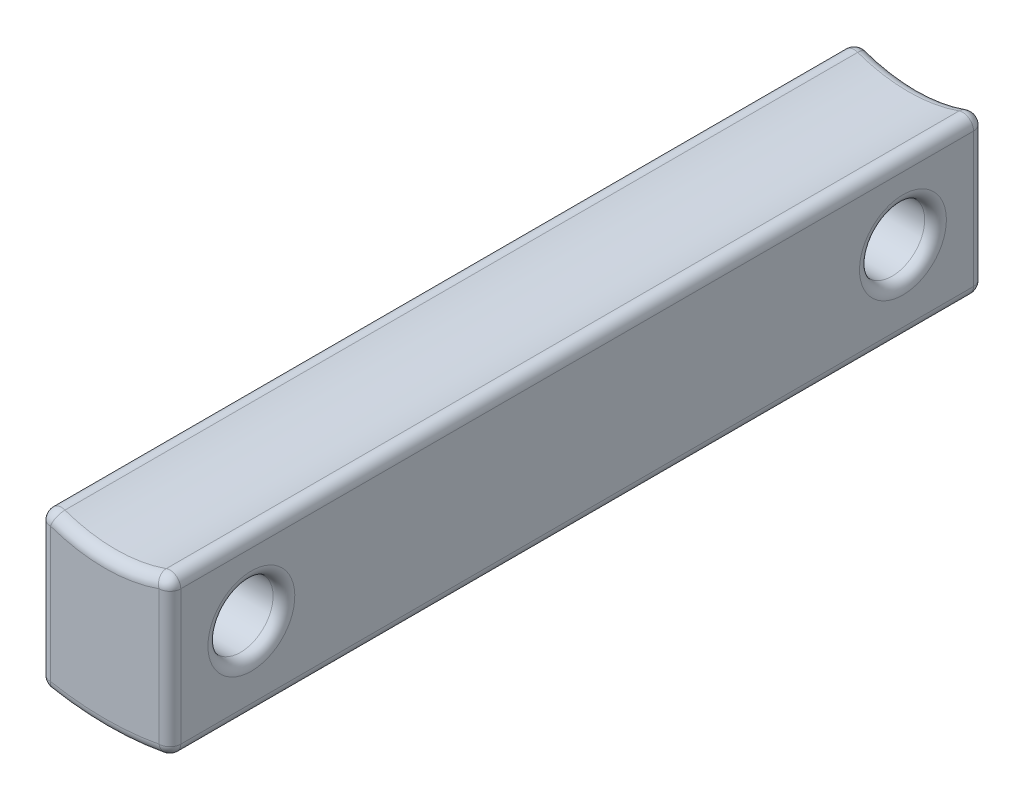
SolidWorks part; units mm, degrees
ref_plane "前视基准面" through (0, 0, 0) normal (0, 0, 1) x (1, 0, 0)
ref_plane "上视基准面" through (0, 0, 0) normal (0, 1, 0) x (1, 0, 0)
ref_plane "右视基准面" through (0, 0, 0) normal (1, 0, 0) x (0, 0, -1)
sketch "草图1" plane through (0, 0, 0) normal (0, 0, 1) x (1, 0, 0)
  line L0 (-28.1607, 0) -> (27.7763, 0) construction
  line L1 (-7.744, -26.8151) -> (-7.744, -12.1147) construction
  line L2 (-13.744, 3.2632) -> (-13.744, -11.4373)
  line L3 (-1.744, -11.4373) -> (-1.744, 3.2632)
  arc A0 (-13.744, 3.2632) -> (-1.744, 3.2632) centre (-7.744, 15.9123) ccw
  arc A1 (-13.744, -11.4373) -> (-1.744, -11.4373) centre (-7.744, 15.9123) ccw
  point P11 (12.9751, -11.4373)
  point P12 (-7.744, 1.9123)
  point P13 (-7.744, -12.0877)
  dimension "D1" = 14
  dimension "D2" = 28
  dimension "D3" = 12
  dimension "D4" = 14
extrude "凸台-拉伸1" add sketch "草图1" along normal mid plane 75
sketch "草图2" plane through (-13.744, 0, 0) normal (-1, 0, 0) x (0, 0, 1)
  line L0 (0, 8.5144) -> (0, -17.1788) construction
  circle A0 centre (30, -4.0521) radius 3
  circle A1 centre (-30, -4.0521) radius 3
  dimension "D1" = 6
  dimension "D2" = 60
extrude "切除-拉伸1" cut sketch "草图2" against normal through all
fillet "圆角1" radius 1 14 edges at (-13.744, -4.087, 37.5) (-1.744, -4.087, 37.5) (-1.744, -4.0521, -27) (-1.744, -4.0521, 33) (-13.744, -4.087, -37.5) (-1.744, -4.087, -37.5) (-13.744, -11.4373, 0) (-7.744, -12.0877, 37.5) (-1.744, -11.4373, 0) (-7.744, -12.0877, -37.5) (-1.744, 3.2632, 0) (-7.744, 1.9123, 37.5) (-13.744, 3.2632, 0) (-7.744, 1.9123, -37.5)
